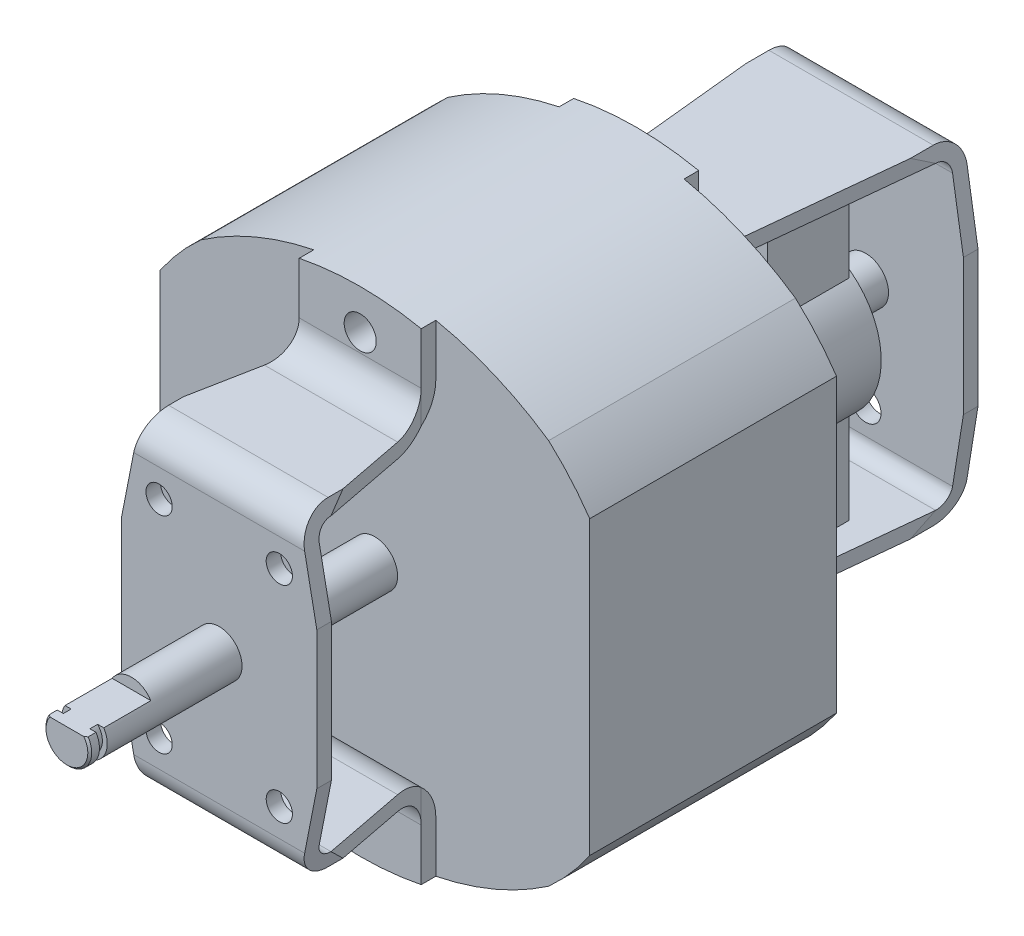
SolidWorks part; units mm, degrees
material "PW50:12:C1:0:1:2:Re:26:"
ref_plane "Plane1" through (0, 0, 0) normal (0, 0, 1) x (1, 0, 0)
ref_plane "Plane2" through (0, 0, 0) normal (0, 1, 0) x (1, 0, 0)
ref_plane "Plane3" through (0, 0, 0) normal (1, 0, 0) x (0, 0, -1)
other "Configuration Table"
sketch "motor core shape" plane through (0, 0, 0) normal (0, 0, 1) x (1, 0, 0)
  line L0 (-5.8998, 26.05) -> (5.8998, 26.05)
  line L1 (-22.1, 15) -> (-22.1, -15)
  line L2 (5.8998, -26.05) -> (-5.8998, -26.05)
  line L3 (22.1, -15) -> (22.1, 15)
  arc A0 (-5.8998, 26.05) -> (-22.1, 15) centre (0, 0) ccw
  arc A1 (-22.1, -15) -> (-5.8998, -26.05) centre (0, 0) ccw
  arc A2 (5.8998, -26.05) -> (22.1, -15) centre (0, 0) ccw
  arc A3 (22.1, 15) -> (5.8998, 26.05) centre (0, 0) ccw
  dimension "D1" = 44.2
  dimension "D2" = 52.1
  dimension "D3" = 30
  dimension "D4" = 11.7996
extrude "motor core" add sketch "motor core shape" along normal blind 25.38
sketch "Sketch5" plane through (0, 0, 25.38) normal (0, 0, 1) x (1, 0, 0)
  line L0 (0, 30.7658) -> (0, -31.4186) construction
  line L1 (-27.6647, 0) -> (27.0118, 0) construction
  line L2 (-5.8998, 26.05) -> (5.8998, 26.05) construction
  line L5 (8.2, 16.45) -> (10.04, 7.075)
  line L6 (-8.2, 16.45) -> (-10.04, 7.075)
  line L7 (10.04, 7.075) -> (10.04, -7.075)
  line L8 (-10.04, 7.075) -> (-10.04, -7.075)
  line L9 (-8.2, -16.45) -> (-10.04, -7.075)
  line L10 (8.2, -16.45) -> (10.04, -7.075)
  line L15 (-8.2, 16.45) -> (8.2, 16.45)
  line L16 (-8.2, -16.45) -> (8.2, -16.45)
  point P9 (0, 25.95)
  point P16 (-10.04, 0)
  point P17 (10.04, 0)
  point P21 (0, -25.95)
  dimension "D1" = 16.4
  dimension "D2" = 9.6
  dimension "D4" = 20.08
  dimension "D5" = 14.15
extrude "gear end plate" add sketch "Sketch5" along normal blind 16
fillet "gear end plate fillet" radius 3 2 edges at (0, -16.45, 41.38) (-8.2, 16.45, 33.38)
sketch "Sketch7" plane through (-10.04, 0, 0) normal (-1, 0, 0) x (0, 0, 1)
  line L0 (25.38, 15) -> (25.38, -15) construction
  line L1 (25.38, 14.95) -> (25.38, -14.95)
  line L5 (38.38, -14.95) -> (25.38, -14.95)
  line L6 (39.88, -13.45) -> (39.88, -7.075)
  line L7 (39.88, 7.075) -> (39.88, -7.075)
  line L8 (39.88, 13.45) -> (39.88, 7.075)
  line L9 (38.38, 14.95) -> (25.38, 14.95)
  line L10 (38.38, -14.95) -> (25.38, -14.95)
  line L11 (39.88, -13.45) -> (39.88, -7.075)
  line L12 (39.88, 7.075) -> (39.88, -7.075)
  line L13 (39.88, 13.45) -> (39.88, 7.075)
  line L14 (38.38, 14.95) -> (25.38, 14.95)
  arc A2 (38.38, -14.95) -> (39.88, -13.45) centre (38.38, -13.45) ccw
  arc A3 (39.88, 13.45) -> (38.38, 14.95) centre (38.38, 13.45) ccw
  arc A4 (38.38, -14.95) -> (39.88, -13.45) centre (38.38, -13.45) ccw
  arc A5 (39.88, 13.45) -> (38.38, 14.95) centre (38.38, 13.45) ccw
  dimension "D1" = 1.5
extrude "gear end plate cut" cut sketch "Sketch7" against normal through all
sketch "Sketch8" plane through (0, 0, 25.38) normal (0, 0, 1) x (1, 0, 0)
  line L0 (0, 16.45) -> (0, -16.45) construction
  line L1 (6.275, 25.95) -> (6.275, 16.45)
  line L2 (-30.1129, 0) -> (30.1129, 0) construction
  line L3 (-6.275, -25.95) -> (-6.275, -16.45)
  line L4 (5.8998, -25.95) -> (-5.8998, -25.95)
  line L5 (6.275, -25.95) -> (-6.275, -25.95)
  line L6 (-6.275, 25.95) -> (-6.275, 16.45)
  line L7 (6.275, -25.95) -> (6.275, -16.45)
  line L8 (8.2, -16.45) -> (-8.2, -16.45) construction
  line L9 (6.275, 16.45) -> (-6.275, 16.45)
  line L10 (6.275, -16.45) -> (-6.275, -16.45)
  line L12 (6.275, 25.95) -> (-6.275, 25.95)
  point P19 (0, 0)
  dimension "D2" = 12.55
  dimension "D1" = 0.1
extrude "gear end plate tabs" add sketch "Sketch8" along normal blind 1.5
sketch "Sketch9" plane through (0, -16.45, 0) normal (0, -1, 0) x (1, 0, 0)
  line L0 (-8.2, 25.38) -> (-6.275, 25.38) construction
  line L1 (6.275, 25.38) -> (8.2, 25.38) construction
  line L2 (-8.4944, 25.38) -> (-6.275, 25.38)
  line L3 (6.275, 25.38) -> (8.4944, 25.38)
  line L6 (-8.4944, 38.38) -> (-8.4944, 25.38) construction
  line L7 (8.4944, 38.38) -> (6.275, 26.88)
  line L8 (-6.275, 26.88) -> (-6.275, 25.38) construction
  line L9 (6.275, 26.88) -> (6.275, 25.38) construction
  line L10 (-6.275, 26.88) -> (-6.275, 25.38)
  line L11 (6.275, 26.88) -> (6.275, 25.38)
  line L12 (-6.275, 26.88) -> (-8.4944, 38.38)
  line L13 (-8.4944, 38.38) -> (-8.4944, 25.38)
  line L14 (8.4944, 38.38) -> (8.4944, 25.38) construction
  line L15 (8.4944, 38.38) -> (8.4944, 25.38)
extrude "gear end side cut" cut sketch "Sketch9" against normal through all
fillet "gear end tab fillet" radius 3 2 edges at (0, -16.45, 26.88) (0, 16.45, 26.88)
sketch "Sketch10" plane through (-6.275, 0, 0) normal (-1, 0, 0) x (0, 0, 1)
  line L0 (25.38, 19.45) -> (25.38, 14.95)
  line L2 (29.88, 14.95) -> (25.38, 14.95)
  line L3 (29.88, -14.95) -> (25.38, -14.95)
  line L4 (25.38, -19.45) -> (25.38, -14.95)
  arc A3 (25.38, 19.45) -> (29.88, 14.95) centre (29.88, 19.45) ccw
  arc A4 (25.38, 19.45) -> (29.88, 14.95) centre (29.88, 19.45) ccw
  arc A5 (29.88, -14.95) -> (25.38, -19.45) centre (29.88, -19.45) ccw
  arc A6 (29.88, -14.95) -> (25.38, -19.45) centre (29.88, -19.45) ccw
  dimension "D1" = 1.5
  dimension "D2" = 1.5
extrude "gear end kludge fillet" cut sketch "Sketch10" against normal through all and the other way through all
sketch "Sketch11" plane through (0, 0, 41.38) normal (0, 0, 1) x (1, 0, 0)
  line L0 (0, -20.7281) -> (0, 30.0313) construction
  line L1 (-15.0973, 0) -> (30.1129, 0) construction
  circle A0 centre (6.1825, 10.5986) radius 1.35
  circle A1 centre (-6.1825, 10.5986) radius 1.35
  circle A2 centre (-6.1825, -10.5986) radius 1.35
  circle A3 centre (6.1825, -10.5986) radius 1.35
  dimension "D1" = 27.24
  dimension "D2" = 2.7
extrude "gear caddy screw holes" cut sketch "Sketch11" against normal up to next
sketch "Sketch13" plane through (0, 0, 0) normal (0, 0, -1) x (-1, 0, 0)
  line L0 (0, 16.95) -> (0, -16.95) construction
  line L1 (-10.05, 0) -> (10.05, 0) construction
  line L2 (-8.45, 16.95) -> (8.45, 16.95)
  line L3 (8.45, 16.95) -> (10.05, 7)
  line L4 (-10.05, 7) -> (-10.05, -7)
  line L5 (10.05, 7) -> (10.05, -7)
  line L6 (-8.45, 16.95) -> (-10.05, 7)
  line L7 (-8.45, -16.95) -> (-10.05, -7)
  line L8 (8.45, -16.95) -> (10.05, -7)
  line L9 (-8.45, -16.95) -> (8.45, -16.95)
  point P5 (-10.05, 0)
  point P10 (0, 16.45)
  point P12 (0, 16.95)
  point P15 (-10.04, 0)
  point P16 (10.04, 0)
  point P17 (10.05, 0)
  point P18 (0, -16.45)
  point P19 (0, -16.95)
  dimension "D1" = 14
  dimension "D2" = 33.9
  dimension "D3" = 16.9
  dimension "D4" = 20.1
extrude "rotor end plate" add sketch "Sketch13" along normal blind 26.6
fillet "rotor end plate fillet" radius 3 2 edges at (0, 16.95, -26.6) (8.45, -16.95, -13.3)
sketch "Sketch14" plane through (10.05, 0, 0) normal (1, 0, 0) x (0, 0, -1)
  line L0 (0, -15) -> (0, 15) construction
  line L1 (0, -15.45) -> (0, 15.45)
  line L5 (23.6, -15.45) -> (0, -15.45)
  line L6 (25.1, -13.95) -> (25.1, -7)
  line L7 (25.1, 7) -> (25.1, -7)
  line L8 (25.1, 13.95) -> (25.1, 7)
  line L9 (23.6, 15.45) -> (0, 15.45)
  line L10 (23.6, -15.45) -> (0, -15.45)
  line L11 (25.1, -13.95) -> (25.1, -7)
  line L12 (25.1, 7) -> (25.1, -7)
  line L13 (25.1, 13.95) -> (25.1, 7)
  line L14 (23.6, 15.45) -> (0, 15.45)
  arc A2 (23.6, -15.45) -> (25.1, -13.95) centre (23.6, -13.95) ccw
  arc A3 (25.1, 13.95) -> (23.6, 15.45) centre (23.6, 13.95) ccw
  arc A4 (23.6, -15.45) -> (25.1, -13.95) centre (23.6, -13.95) ccw
  arc A5 (25.1, 13.95) -> (23.6, 15.45) centre (23.6, 13.95) ccw
  dimension "D1" = 1.5
extrude "rotor end plate cut" cut sketch "Sketch14" against normal through all and the other way through all
sketch "Sketch15" plane through (0, 0, 0) normal (0, 0, -1) x (-1, 0, 0)
  line L0 (-6.425, 25.95) -> (6.425, 25.95)
  line L1 (-6.425, 25.95) -> (-6.425, 16.95)
  line L2 (-8.45, 16.95) -> (8.45, 16.95) construction
  line L3 (-6.425, 16.95) -> (6.425, 16.95)
  line L4 (0, 30.1945) -> (0, -31.9899) construction
  line L5 (-30.3577, 0) -> (31.9899, 0) construction
  line L6 (6.425, 25.95) -> (6.425, 16.95)
  line L7 (6.425, -25.95) -> (6.425, -16.95)
  line L8 (-6.425, -16.95) -> (6.425, -16.95)
  line L9 (-6.425, -25.95) -> (-6.425, -16.95)
  line L10 (-6.425, -25.95) -> (6.425, -25.95)
  line L11 (5.8998, 26.05) -> (-5.8998, 26.05) construction
  point P13 (0, 16.95)
  point P14 (0, 25.95)
  point P18 (0, -25.95)
  point P19 (0, -16.95)
  dimension "D1" = 12.85
  dimension "D2" = 0.1
extrude "rotor end plate tabs" add sketch "Sketch15" along normal blind 1.5
sketch "Sketch16" plane through (0, -16.95, 0) normal (0, -1, 0) x (1, 0, 0)
  line L2 (-8.6912, -23.6) -> (-8.6912, 0) construction
  line L3 (-6.425, -1.5) -> (-6.425, 0) construction
  line L4 (6.425, -1.5) -> (6.425, 0) construction
  line L5 (8.6912, -23.6) -> (8.6912, 0) construction
  line L6 (-8.6912, -23.6) -> (-8.6912, 0)
  line L7 (-6.425, -1.5) -> (-6.425, 0)
  line L8 (6.425, -1.5) -> (6.425, 0)
  line L9 (8.6912, -23.6) -> (8.6912, 0)
  line L10 (8.6912, 0) -> (6.425, 0)
  line L11 (6.425, -1.5) -> (8.6912, -23.6)
  line L12 (-6.425, 0) -> (-8.6912, 0)
  line L13 (-6.425, -1.5) -> (-8.6912, -23.6)
extrude "rotor end side ct" cut sketch "Sketch16" against normal through all and the other way through all
fillet "rotor end tab fillet" radius 3 2 edges at (0, -16.95, -1.5) (0, 16.95, -1.5)
sketch "Sketch17" plane through (-6.425, 0, 0) normal (-1, 0, 0) x (0, 0, 1)
  line L0 (0, 19.95) -> (0, 15.45)
  line L2 (-4.5, 15.45) -> (0, 15.45)
  line L3 (0, -19.95) -> (0, -15.45)
  line L5 (-4.5, -15.45) -> (0, -15.45)
  arc A1 (-4.5, 15.45) -> (0, 19.95) centre (-4.5, 19.95) ccw
  arc A2 (-4.5, 15.45) -> (0, 19.95) centre (-4.5, 19.95) ccw
  arc A3 (0, -19.95) -> (-4.5, -15.45) centre (-4.5, -19.95) ccw
  arc A4 (0, -19.95) -> (-4.5, -15.45) centre (-4.5, -19.95) ccw
  dimension "D1" = 1.5
  dimension "D2" = 1.5
extrude "rotor end kludge fillet" cut sketch "Sketch17" against normal through all and the other way through all
sketch "Sketch12" plane through (0, 0, 0) normal (0, 0, -1) x (-1, 0, 0)
  line L0 (-28.8072, 0) -> (27.0118, 0) construction
  line L1 (5.8998, 26.05) -> (-5.8998, 26.05) construction
  circle A0 centre (0, 21.3) radius 1.65
  circle A1 centre (0, -21.3) radius 1.65
  dimension "D1" = 3.3
  dimension "D2" = 4.75
extrude "motor long screw holes" cut sketch "Sketch12" against normal through all and the other way through all
sketch "Sketch1" plane through (0, 0, 25.38) normal (0, 0, 1) x (1, 0, 0)
  circle A0 centre (0, 0) radius 2.35
  dimension "D1" = 4.7
extrude "motor shaft" add sketch "Sketch1" along normal blind 31.66 and the other way offset from surface (54.08 mm away) 28.7 other way up to face at (0, -26.0004, 0)
sketch "Sketch3" plane through (0, 0, 57.04) normal (0, 0, 1) x (1, 0, 0)
  circle A0 centre (0, 0) radius 2.35 construction
  circle A1 centre (0, 0) radius 1.85
  circle A2 centre (0, 0) radius 1.85
  circle A3 centre (0, 0) radius 2.35
  dimension "D1" = 0.5
extrude "groove cut" cut sketch "Sketch3" against normal blind 1.8
sketch "Sketch4" plane through (0, 0, 57.04) normal (0, 0, 1) x (1, 0, 0)
  circle A0 centre (0, 0) radius 2.35 construction
  circle A1 centre (0, 0) radius 2.35
extrude "groove fill" add sketch "Sketch4" against normal offset from surface (1 mm away) 0.8 up to face at (1.85, 0, 55.24)
chamfer "shaft chamfer" distance 0.2 angle 45 1 edges at (2.35, 0, 57.04)
sketch "Sketch2" plane through (0, 0, 57.04) normal (0, 0, 1) x (1, 0, 0)
  line L0 (-1.99, 1.25) -> (1.99, 1.25)
  circle A0 centre (0, 0) radius 2.35 construction
  arc A1 (1.99, 1.25) -> (-1.99, 1.25) centre (0, 0) ccw
  dimension "D1" = 3.6
extrude "motor gear flat" cut sketch "Sketch2" against normal blind 6.64
sketch "Sketch18" plane through (0, 0, -26.6) normal (0, 0, -1) x (-1, 0, 0)
  line L0 (-33.3772, 0) -> (32.8875, 0) construction
  circle A0 centre (0, 11.12) radius 1.58
  circle A1 centre (0, -11.12) radius 1.58
  dimension "D1" = 3.16
  dimension "D2" = 25.4
extrude "rotor end plate holes" cut sketch "Sketch18" against normal up to next
ref_plane "Plane4" through (0, 0, -18.7) normal (0, 0, -1) x (-1, 0, 0)
sketch "Sketch20" plane through (0, 0, -18.7) normal (0, 0, -1) x (-1, 0, 0)
  circle A1 centre (0, 0) radius 2.35 construction
  circle A2 centre (0, 0) radius 2.35
  circle A3 centre (0, 0) radius 8
  dimension "D1" = 16
extrude "motor rotor" add sketch "Sketch20" against normal blind 12
sketch "Sketch21" plane through (0, 16.95, 0) normal (0, 1, 0) x (-1, 0, 0)
  line L0 (0, 0) -> (0, -32.7148) construction
  line L1 (0, 0) -> (0, -6.7) construction
  line L2 (5.1372, -18.2466) -> (-5.1372, -18.2466)
  line L3 (-5.1372, -18.2466) -> (-5.1372, -9.8593)
  line L4 (5.1372, -18.2466) -> (5.1372, -9.8593)
  line L5 (-5.1372, -9.8593) -> (5.1372, -9.8593)
  point P8 (0, -18.2466)
  point P11 (0, -9.8593)
extrude "motor stator,brushes" add sketch "Sketch21" along normal up to surface (33.9 mm away)
sketch "Sketch22" plane through (0, 0, 26.88) normal (0, 0, 1) x (1, 0, 0)
  line L0 (0, 0) -> (15.3278, 0) construction
  line L1 (28.8072, 0) -> (-27.0118, 0) construction
  line L3 (-5.8998, 26.05) -> (6.425, 25.9255)
  line L4 (-5.8998, -26.05) -> (6.425, -25.9255)
  arc A0 (31.4115, -2.6863) -> (-31.3668, -2.3101) centre (0, -6.2245) ccw construction
  arc A1 (17.8771, -19.8448) -> (6.425, -25.9255) centre (0, 0) cw
  arc A2 (-5.8998, -26.05) -> (-17.8771, -19.8448) centre (0, 0) cw
  arc A3 (17.8771, 19.8448) -> (-17.8771, 19.8448) centre (0, -6.2245) ccw
  arc A4 (-5.8998, 26.05) -> (-6.3251, 25.95) centre (0, 0) ccw construction
  arc A5 (-5.8998, 26.05) -> (-17.8771, 19.8448) centre (0, 0) ccw
  arc A6 (22.1, 15) -> (6.425, 25.9255) centre (0, 0) ccw construction
  arc A7 (17.8771, 19.8448) -> (6.425, 25.9255) centre (0, 0) ccw
  arc A8 (17.8771, -19.8448) -> (-17.8771, -19.8448) centre (0, 6.2245) cw
extrude "Cut-Extrude1" cut sketch "Sketch22" against normal through all
